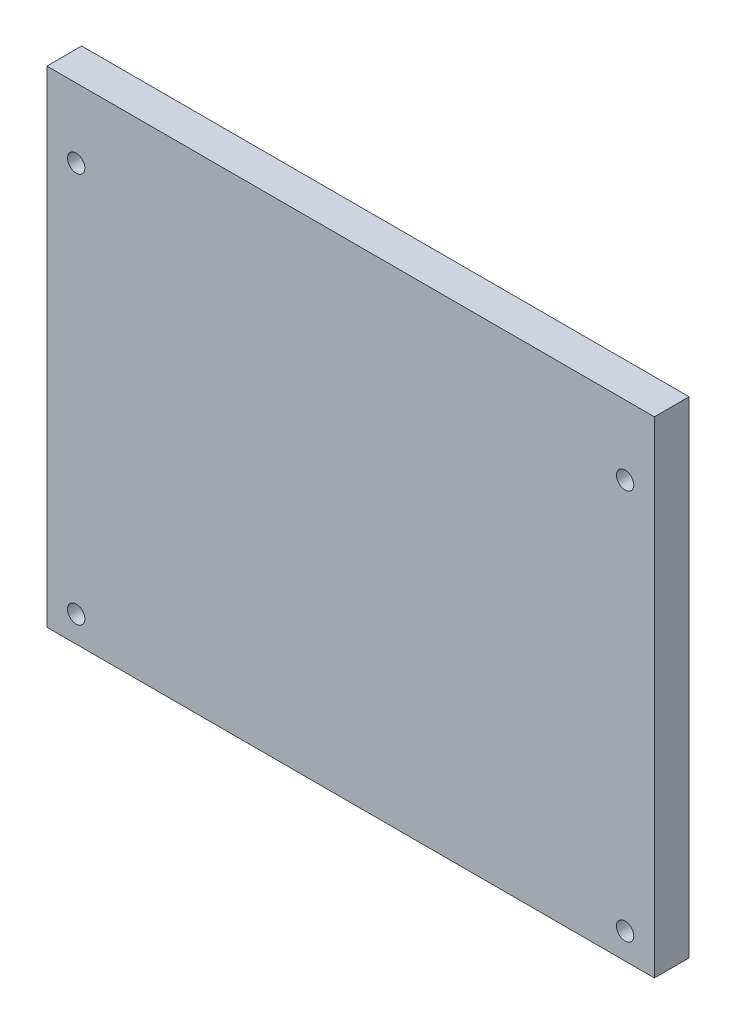
SolidWorks part; units mm, degrees
ref_plane "Front Plane" through (0, 0, 0) normal (0, 0, 1) x (1, 0, 0)
ref_plane "Top Plane" through (0, 0, 0) normal (0, 1, 0) x (1, 0, 0)
ref_plane "Right Plane" through (0, 0, 0) normal (1, 0, 0) x (0, 0, -1)
sketch "Sketch1" plane through (0, 0, 0) normal (0, 0, 1) x (1, 0, 0)
  line L1 (0, 0) -> (444.5, 0)
  line L2 (0, 0) -> (0, 355.6)
  line L3 (0, 355.6) -> (444.5, 355.6)
  line L4 (444.5, 0) -> (444.5, 355.6)
extrude "Boss-Extrude1" add sketch "Sketch1" along normal blind 25.4
sketch "Sketch2" plane through (0, 0, 0) normal (0, 0, 1) x (1, 0, 0)
  circle A0 centre (21.4376, 19.05) radius 6.35
  circle A1 centre (423.0624, 19.05) radius 6.35
  circle A2 centre (21.4376, 304.8) radius 6.35
  circle A3 centre (423.0624, 304.8) radius 6.35
extrude "Cut-Extrude1" cut sketch "Sketch2" along normal through all
sketch "Sketch3" plane through (0, 0, 0) normal (0, 0, 1) x (1, 0, 0)
  circle A0 centre (172.2374, 196.85) radius 6.7437
  circle A1 centre (178.9811, 196.85) radius 5.5626
  circle A2 centre (173.4185, 44.45) radius 5.5626
  circle A3 centre (178.9811, 44.45) radius 5.5626
